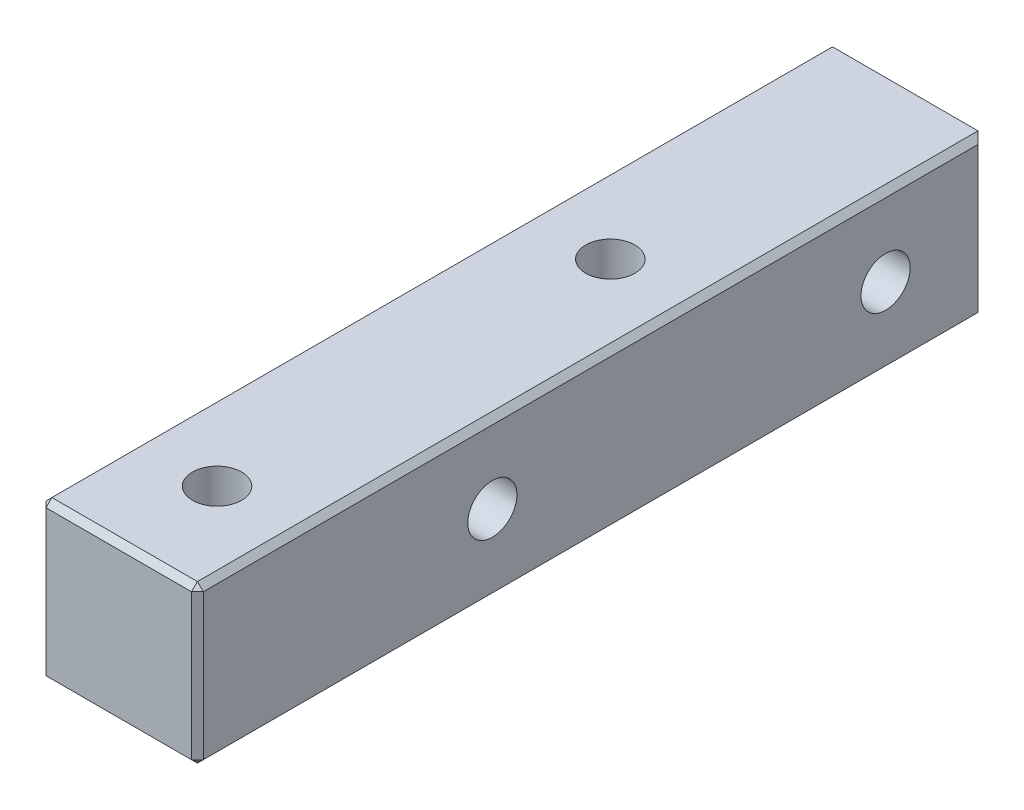
SolidWorks part; units mm, degrees
material "6061 合金"
ref_plane "前视基准面" through (0, 0, 0) normal (0, 0, 1) x (1, 0, 0)
ref_plane "上视基准面" through (0, 0, 0) normal (0, 1, 0) x (1, 0, 0)
ref_plane "右视基准面" through (0, 0, 0) normal (1, 0, 0) x (0, 0, -1)
sketch "草图1" plane through (0, 0, 0) normal (0, 0, 1) x (1, 0, 0)
  line L1 (-4, -4) -> (4, -4)
  line L2 (-4, -4) -> (-4, 4)
  line L3 (-4, 4) -> (4, 4)
  line L4 (4, -4) -> (4, 4)
  line L5 (0, 4) -> (0, -4) construction
  line L6 (-4, 0) -> (4, 0) construction
  point P0 (0, 0)
  dimension "D1" = 8
extrude "凸台-拉伸1" add sketch "草图1" along normal mid plane 40
sketch "草图2" plane through (-4, 0, 0) normal (-1, 0, 0) x (0, 0, 1)
  line L0 (-15, 0) -> (5, 0) construction
  line L1 (-20, 4) -> (-20, -4) construction
  dimension "D1" = 5
  dimension "D2" = 20
sketch "草图3" plane through (0, 4, 0) normal (0, 1, 0) x (1, 0, 0)
  line L0 (0, -15) -> (0, 5) construction
  line L1 (4, -20) -> (-4, -20) construction
  dimension "D1" = 5
  dimension "D2" = 20
hole_wizard " 螺纹孔1" positions "草图4" profile "草图5" tap size "M3" standard "GB" end condition up to next
sketch "草图4" plane through (-4, 0, 0) normal (-1, 0, 0) x (0, 0, 1)
  point P0 (-15, 0)
  point P3 (5, 0)
sketch "草图5" plane through (-4, 0, -15) normal (0, 1, 0) x (0, 0, 1)
  line L0 (0, 0) -> (0, 8)
  line L1 (0, 8) -> (1.25, 8)
  line L2 (1.25, 8) -> (1.25, 0)
  line L5 (1.25, 0) -> (0, 0)
  line L11 (0, -6.35) -> (0, 107.95) construction
  dimension "通孔螺纹孔钻头直径" = 2.5
  dimension "通孔螺纹孔钻头深度" = 8
cosmetic thread "孔螺蚊线1" parameters "D2"=3
cosmetic thread "孔螺蚊线2" parameters "D2"=3
hole_wizard " 螺纹孔2" positions "草图6" profile "草图7" tap size "M3" standard "GB" end condition up to next
sketch "草图6" plane through (0, 4, 0) normal (0, 1, 0) x (1, 0, 0)
  point P0 (0, 5)
  point P3 (0, -15)
sketch "草图7" plane through (0, 4, -5) normal (1, 0, 0) x (0, 0, 1)
  line L0 (0, 0) -> (0, 8)
  line L1 (0, 8) -> (1.25, 8)
  line L2 (1.25, 8) -> (1.25, 0)
  line L5 (1.25, 0) -> (0, 0)
  line L11 (0, -6.35) -> (0, 107.95) construction
  dimension "通孔螺纹孔钻头直径" = 2.5
  dimension "通孔螺纹孔钻头深度" = 8
cosmetic thread "孔螺蚊线3" parameters "D2"=3
cosmetic thread "孔螺蚊线4" parameters "D2"=3
chamfer "倒角1" distance 0.3 angle 45 11 edges at (-4, -4, 0) (4, 0, 20) (4, -4, 0) (0, -4, 20) (0, -4, -20) (-4, 0, -20) (4, 0, -20) (4, 4, 0) (0, 4, 20) (-4, 0, 20) (-4, 4, 0)
